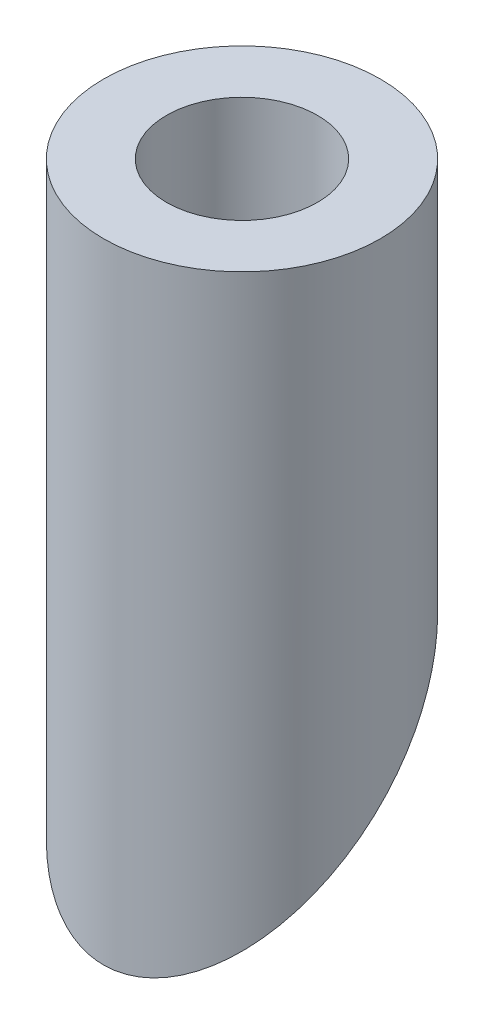
SolidWorks part; units mm, degrees
ref_plane "前视基准面" through (0, 0, 0) normal (0, 0, 1) x (1, 0, 0)
ref_plane "上视基准面" through (0, 0, 0) normal (0, 1, 0) x (1, 0, 0)
ref_plane "右视基准面" through (0, 0, 0) normal (1, 0, 0) x (0, 0, -1)
sketch "草图1" plane through (0, 0, 0) normal (0, 1, 0) x (1, 0, 0)
  circle A0 centre (0, 0) radius 6
  circle A1 centre (0, 0) radius 11
  dimension "D1" = 12
  dimension "D2" = 22
extrude "凸台-拉伸1" add sketch "草图1" along normal blind 50
sketch "草图2" plane through (0, 0, 0) normal (1, 0, 0) x (0, 0, -1)
  line L0 (-11, 0) -> (11, 22)
  line L1 (11, 0) -> (11, 50) construction
  line L2 (-11, 0) -> (11, 0) construction
  line L3 (-11, 0) -> (11, 0)
  line L4 (11, 22) -> (11, 0)
  dimension "D1" = 45
extrude "切除-拉伸1" cut sketch "草图2" against normal through all both and the other way through all
